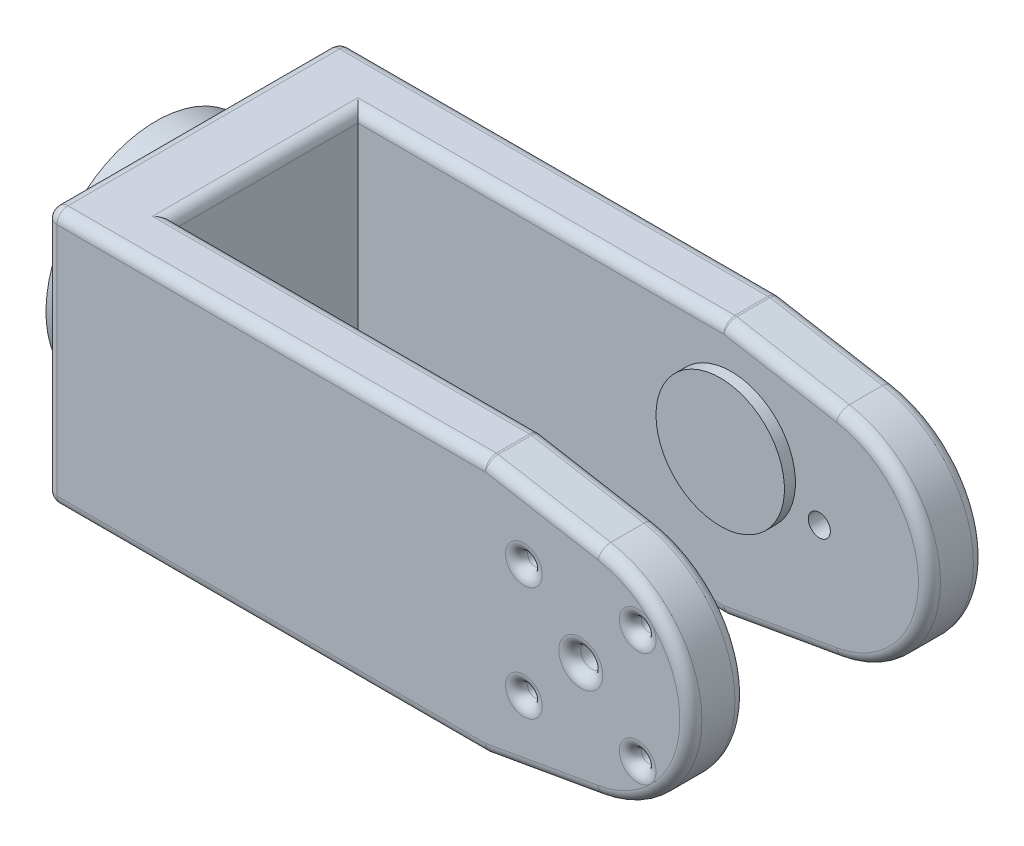
SolidWorks part; units mm, degrees
ref_plane "Front Plane" through (0, 0, 0) normal (0, 0, 1) x (1, 0, 0)
ref_plane "Top Plane" through (0, 0, 0) normal (0, 1, 0) x (1, 0, 0)
ref_plane "Right Plane" through (0, 0, 0) normal (1, 0, 0) x (0, 0, -1)
sketch "Sketch1" plane through (0, 0, 0) normal (0, 0, 1) x (1, 0, 0)
  line L1 (109.1806, -50.9004) -> (140.1218, -45.4447)
  line L2 (140.1218, 13.6438) -> (109.1806, 19.0996)
  line L3 (109.1806, 19.0996) -> (-10.8194, 19.0996)
  line L4 (-10.8194, 19.0996) -> (-10.8194, -50.9004)
  line L6 (109.1806, -50.9004) -> (-10.8194, -50.9004)
  arc A0 (140.1218, -45.4447) -> (140.1218, 13.6438) centre (134.9123, -15.9004) ccw
  dimension "D4" = 30
  dimension "D1" = 170
  dimension "D2" = 170
  dimension "D3" = 70
  dimension "D5" = 120
  dimension "D6" = 120
extrude "Boss-Extrude1" add sketch "Sketch1" along normal mid plane 80 contours L3 L4 L6 L1 A0 L2
sketch "Sketch2" plane through (0, 19.0996, 0) normal (0, 1, 0) x (1, 0, 0)
  line L0 (-10.8194, -40) -> (-10.8194, 40) construction
  line L1 (9.1806, 25) -> (209.0654, 25)
  line L2 (9.1806, 25) -> (9.1806, -25)
  line L3 (9.1806, -25) -> (209.0654, -25)
  line L4 (209.0654, 25) -> (209.0654, -25)
  line L5 (109.1806, 40) -> (-10.8194, 40) construction
  line L6 (109.1806, -40) -> (-10.8194, -40) construction
  dimension "D1" = 20
  dimension "D2" = 15
  dimension "D3" = 15
extrude "Cut-Extrude1" cut sketch "Sketch2" against normal through all
sketch "Sketch3" plane through (0, 0, 25) normal (0, 0, -1) x (-1, 0, 0)
  circle A0 centre (-110.8996, -9.1454) radius 17.5
  dimension "D1" = 35
extrude "Boss-Extrude2" add sketch "Sketch3" along normal blind 3
mirror "Mirror1" about plane through (0, 0, 0) normal (0, 0, 1) of "Boss-Extrude2"
sketch "Sketch4" plane through (0, 0, 40) normal (0, 0, 1) x (1, 0, 0)
  circle A0 centre (150.4123, -0.4004) radius 2
  circle A1 centre (119.4123, -0.4004) radius 2
  circle A2 centre (150.4123, -31.4004) radius 2
  circle A3 centre (119.4123, -31.4004) radius 2
  dimension "D1" = 4
  dimension "D2" = 4
  dimension "D3" = 4
  dimension "D4" = 4
  dimension "D5" = 31
  dimension "D6" = 31
  dimension "D7" = 15.5
  dimension "D8" = 15.5
extrude "Cut-Extrude2" cut sketch "Sketch4" against normal blind 10 contours A0 | A2 | A3 | A1
sketch "Sketch5" plane through (0, 0, 40) normal (0, 0, 1) x (1, 0, 0)
  circle A0 centre (134.9123, -15.9004) radius 3
  dimension "D1" = 6
extrude "Cut-Extrude3" cut sketch "Sketch5" against normal through all
sketch "Sketch6" plane through (-10.8194, 0, 0) normal (-1, 0, 0) x (0, 0, 1)
  line L0 (40, -50.9004) -> (-40, -50.9004) construction
  circle A0 centre (0, -15.9004) radius 30
  dimension "D1" = 60
  dimension "D2" = 35
extrude "Boss-Extrude3" add sketch "Sketch6" along normal blind 10 contours A0
sketch "Sketch8" plane through (-20.8194, 0, 0) normal (-1, 0, 0) x (0, 0, 1)
  circle A2 centre (0, -15.9004) radius 25
  circle A3 centre (0, -15.9004) radius 25
  dimension "D1" = 5
extrude "Boss-Extrude4" add sketch "Sketch8" along normal blind 3
fillet "Fillet1" radius 3 36 edges at (124.6512, 16.3717, -25) (124.6512, 16.3717, 25) (124.6512, -48.1725, -25) (124.6512, -48.1725, 25) (164.9123, -15.9004, 25) (164.9123, -15.9004, -25) (109.1806, -50.9004, -32.5) (-10.8194, -50.9004, 0) (109.1806, -50.9004, 32.5) (59.1806, -50.9004, 25) (9.1806, -50.9004, 0) (59.1806, -50.9004, -25) (164.9123, -15.9004, 40) (124.6512, -48.1725, 40) (49.1806, -50.9004, 40) (-10.8194, -15.9004, 40) (124.6512, 16.3717, 40) (152.4123, -0.4004, 40) (152.4123, -31.4004, 40) (121.4123, -31.4004, 40) (121.4123, -0.4004, 40) (137.9123, -15.9004, 40) (-10.8194, -15.9004, -40) (49.1806, -50.9004, -40) (124.6512, -48.1725, -40) (164.9123, -15.9004, -40) (124.6512, 16.3717, -40) (137.9123, -15.9004, -40) (59.1806, 19.0996, 25) (109.1806, 19.0996, 32.5) (49.1806, 19.0996, 40) (-10.8194, 19.0996, 0) (49.1806, 19.0996, -40) (109.1806, 19.0996, -32.5) (59.1806, 19.0996, -25) (9.1806, 19.0996, 0)
